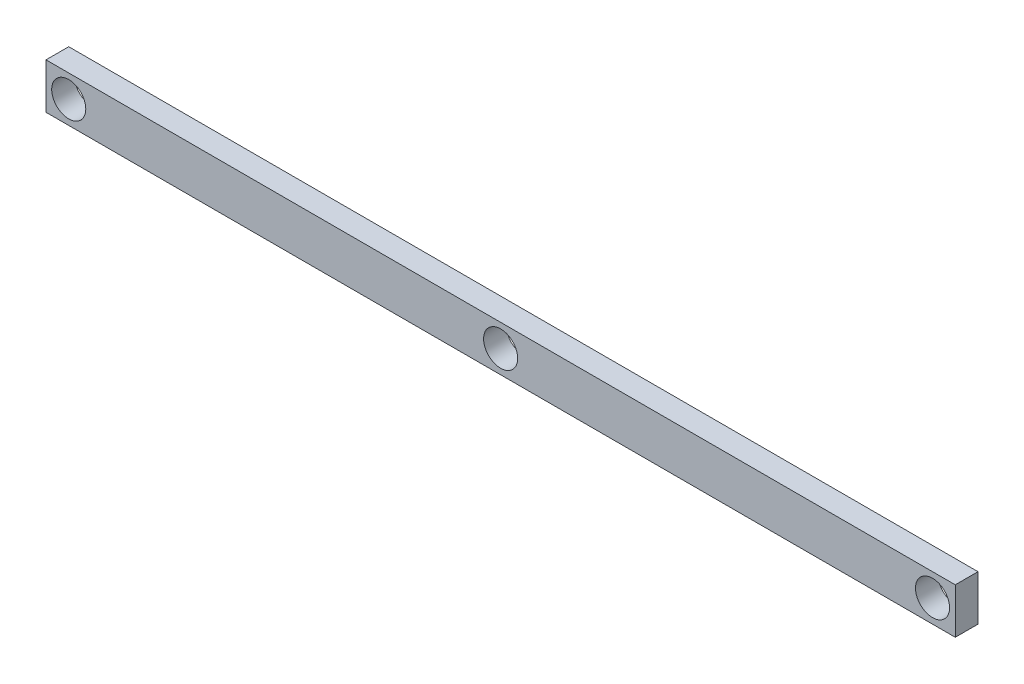
SolidWorks part; units mm, degrees
ref_plane "Front Plane" through (0, 0, 0) normal (0, 0, 1) x (1, 0, 0)
ref_plane "Top Plane" through (0, 0, 0) normal (0, 1, 0) x (1, 0, 0)
ref_plane "Right Plane" through (0, 0, 0) normal (1, 0, 0) x (0, 0, -1)
sketch "Sketch1" plane through (0, 0, 0) normal (0, 1, 0) x (1, 0, 0)
  line L1 (0, 0) -> (40, 0)
  line L2 (0, 0) -> (0, 10)
  line L3 (0, 10) -> (40, 10)
  line L4 (40, 0) -> (40, 10)
  dimension "D1" = 10
  dimension "D2" = 40
extrude "Boss-Extrude1" add sketch "Sketch1" along normal blind 2
sketch "Sketch4" plane through (0, 2, 0) normal (0, 1, 0) x (1, 0, 0)
  line L1 (0, 10) -> (0, 0) construction
  line L2 (0, 10) -> (0, 1)
  line L3 (0, 10) -> (40, 10)
  line L4 (40, 0) -> (40, 10) construction
  line L5 (40, 10) -> (40, 1)
  line L6 (40, 1) -> (0, 1)
  dimension "D2" = 9
extrude "Cut-Extrude2" cut sketch "Sketch4" against normal blind 2
sketch "Sketch5" plane through (0, 0, 0) normal (0, 0, 1) x (1, 0, 0)
  circle A0 centre (20, 1) radius 0.75
  circle A1 centre (1, 1) radius 0.75
  circle A2 centre (39, 1) radius 0.75
  dimension "D1" = 1.5
  dimension "D3" = 1.5
  dimension "D2" = 1.5
extrude "Cut-Extrude3" cut sketch "Sketch5" against normal through all
